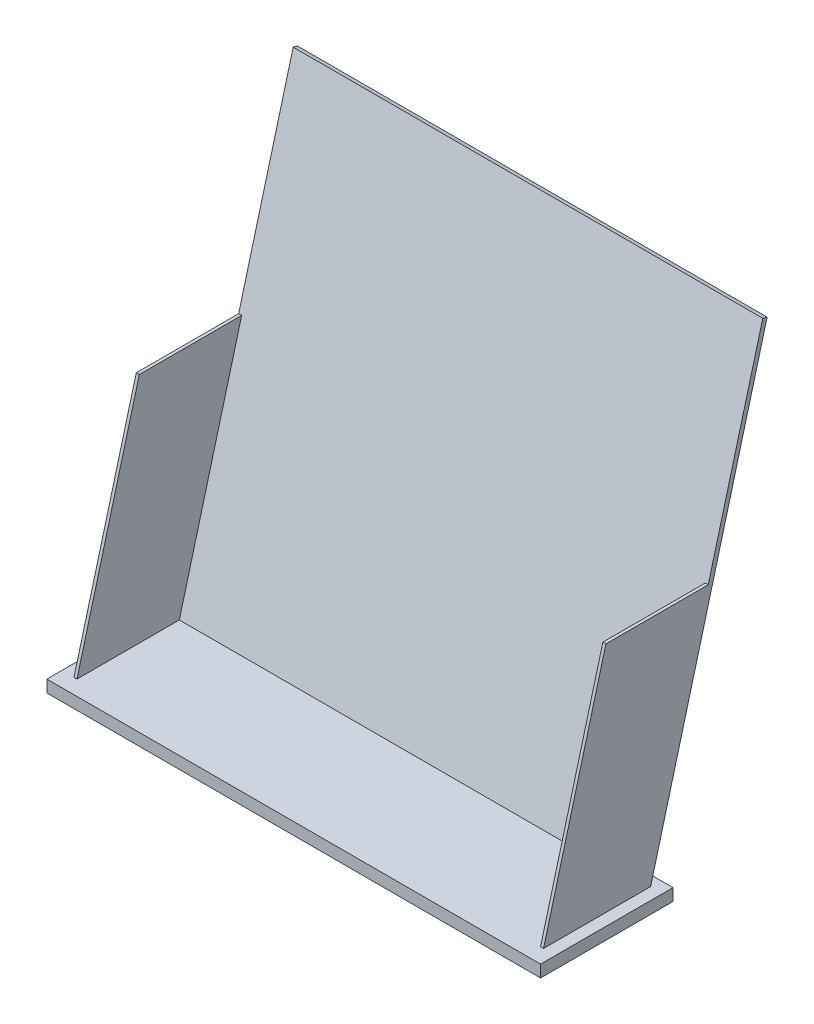
SolidWorks part; units mm, degrees
ref_plane "Front Plane" through (0, 0, 0) normal (0, 0, 1) x (1, 0, 0)
ref_plane "Top Plane" through (0, 0, 0) normal (0, 1, 0) x (1, 0, 0)
ref_plane "Right Plane" through (0, 0, 0) normal (1, 0, 0) x (0, 0, -1)
sketch "Sketch1" plane through (0, 0, 0) normal (0, 1, 0) x (1, 0, 0)
  line L1 (-41, 11) -> (41, 11)
  line L2 (-41, 11) -> (-41, -11)
  line L3 (-41, -11) -> (41, -11)
  line L4 (41, 11) -> (41, -11)
  line L5 (-41, 11) -> (41, -11) construction
  line L6 (-41, -11) -> (41, 11) construction
  point P0 (0, 0)
  dimension "D1" = 82
  dimension "D2" = 22
extrude "Boss-Extrude1" add sketch "Sketch1" along normal blind 2
sketch "Sketch2" plane through (0, 2, 0) normal (0, 1, 0) x (1, 0, 0)
  line L1 (-39, 8.5) -> (39, 8.5) construction
  line L2 (-39, 8.5) -> (-39, -8.5) construction
  line L3 (-39, -8.5) -> (39, -8.5) construction
  line L4 (39, 8.5) -> (39, -8.5) construction
  line L5 (-39, 8.5) -> (39, -8.5) construction
  line L6 (-39, -8.5) -> (39, 8.5) construction
  point P0 (0, 0)
  dimension "D1" = 78
  dimension "D2" = 17
ref_plane "Plane1" through (39, 0, 0) normal (1, 0, 0) x (0, 0, -1)
sketch "Sketch3" plane through (39, 0, 0) normal (1, 0, 0) x (0, 0, -1)
  line L0 (8.5, 2) -> (27.9114, 74.4444)
  line L1 (8.5, 2) -> (-8.5, 2) construction
  line L2 (-8.5, 2) -> (8.5, 2) construction
ref_plane "Plane2" through (-39, 0, 0) normal (1, 0, 0) x (0, 0, -1)
sketch "Sketch4" plane through (-39, 0, 0) normal (1, 0, 0) x (0, 0, -1)
  line L0 (8.5, 2) -> (27.9114, 74.4444)
extrude "Extrude-Thin2" add sketch "Sketch4" along normal blind 78 thin
sketch "Sketch5" plane through (39, 0, 0) normal (1, 0, 0) x (0, 0, -1)
  line L0 (-8.5, 2) -> (1.8528, 40.637)
  line L1 (-8.5, 2) -> (8.5, 2) construction
  line L2 (8.5, 2) -> (-8.5, 2) construction
  line L3 (1.8528, 40.637) -> (18.8528, 40.637)
  line L4 (8.5, 2) -> (27.9114, 74.4444) construction
  line L5 (18.8528, 40.637) -> (8.5, 2)
  line L6 (8.5, 2) -> (-8.5, 2)
extrude "Boss-Extrude2" add sketch "Sketch5" against normal blind 0.5
sketch "Sketch6" plane through (-39, 0, 0) normal (1, 0, 0) x (0, 0, -1)
  line L0 (-8.5, 2) -> (1.8528, 40.637)
  line L1 (1.8528, 40.637) -> (18.8528, 40.637)
  line L2 (18.8528, 40.637) -> (8.5, 2)
  line L3 (8.5, 2) -> (-8.5, 2)
extrude "Boss-Extrude3" add sketch "Sketch6" along normal blind 0.5
ref_plane "Plane3" through (0, 0, 8.5) normal (0, 0, 1) x (1, 0, 0)
ref_plane "Plane4" through (0, 40.64, 0) normal (0, 1, 0) x (1, 0, 0)
sketch "Sketch10" plane through (0, 40.64, 0) normal (0, 1, 0) x (1, 0, 0)
  line L0 (-38.5, 1.8528) -> (38.5, 1.8528)
sketch "Sketch11" plane through (0, 2, 0) normal (0, 1, 0) x (1, 0, 0)
  line L0 (-39, -8.5) -> (39, -8.5)
sketch "Sketch12" plane through (-39, 0, 0) normal (-1, 0, 0) x (0, 0, 1)
  line L0 (-1.8346, 40.5692) -> (8.5, 2)
  line L1 (-1.8528, 40.637) -> (8.5, 2) construction
  line L2 (-8.5, 2) -> (8.5, 2) construction
  line L3 (8.5, -40.9444) -> (8.5, 40.9444) construction
